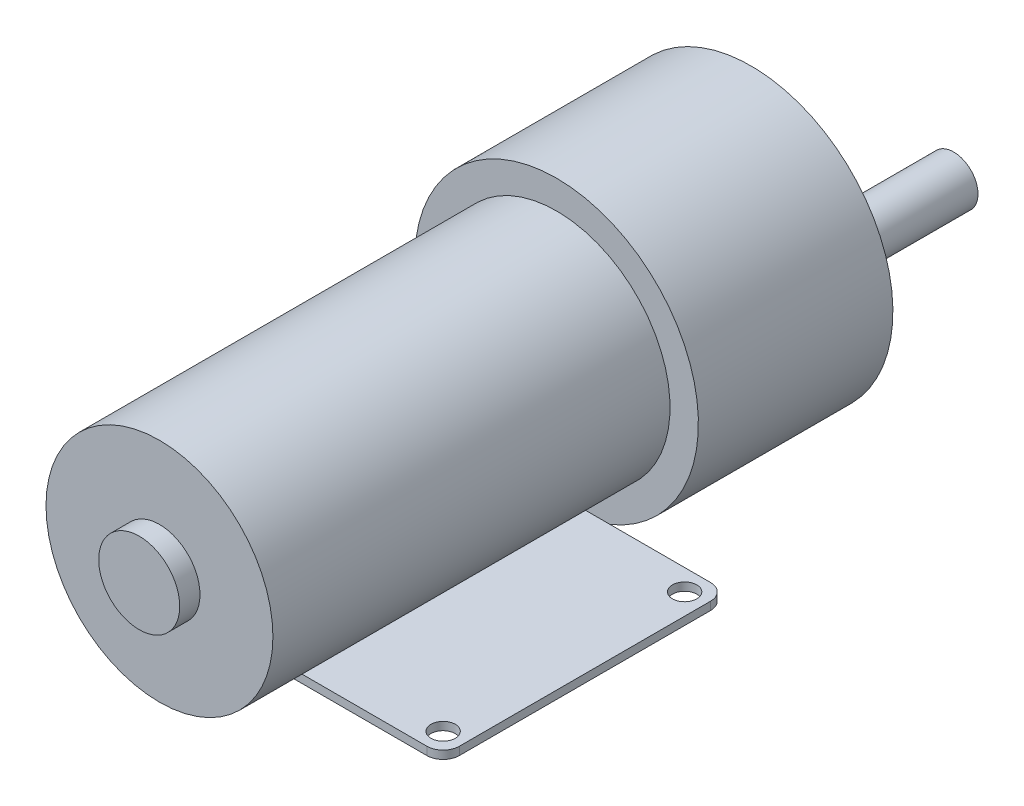
SolidWorks part; units mm, degrees
ref_plane "Plan de face" through (0, 0, 0) normal (0, 0, 1) x (1, 0, 0)
ref_plane "Plan de dessus" through (0, 0, 0) normal (0, 1, 0) x (1, 0, 0)
ref_plane "Plan de droite" through (0, 0, 0) normal (1, 0, 0) x (0, 0, -1)
sketch "Esquisse1" plane through (0, 0, 0) normal (0, 0, 1) x (1, 0, 0)
  circle A0 centre (9.6424, 0) radius 14
  dimension "D1" = 28
extrude "Boss.-Extru.1" add sketch "Esquisse1" along normal blind 49
sketch "Esquisse2" plane through (0, 0, 49) normal (0, 0, 1) x (1, 0, 0)
  circle A0 centre (9.6424, 0) radius 5
  dimension "D1" = 10
extrude "Boss.-Extru.2" add sketch "Esquisse2" along normal blind 2.5
sketch "Esquisse3" plane through (0, 0, 0) normal (0, 0, -1) x (-1, 0, 0)
  circle A0 centre (-9.6424, 0) radius 17.5
extrude "Boss.-Extru.3" add sketch "Esquisse3" along normal blind 24
sketch "Esquisse4" plane through (0, 0, -24) normal (0, 0, -1) x (-1, 0, 0)
  circle A0 centre (-9.6424, -7.2) radius 6
  circle A1 centre (-9.6424, 0) radius 17.5 construction
  dimension "D1" = 12
  dimension "D2" = 7.2
extrude "Boss.-Extru.4" add sketch "Esquisse4" along normal blind 10 contours A0
sketch "Esquisse5" plane through (0, 0, -34) normal (0, 0, -1) x (-1, 0, 0)
  circle A0 centre (-9.6424, -7.2) radius 3
extrude "Boss.-Extru.5" add sketch "Esquisse5" along normal blind 15
sketch "Esquisse7" plane through (0, 0, -49) normal (0, 0, -1) x (-1, 0, 0)
  line L0 (-11.3007, -9.7) -> (-7.9841, -9.7)
  arc A0 (-7.9841, -9.7) -> (-11.3007, -9.7) centre (-9.6424, -7.2) ccw
  circle A1 centre (-9.6424, -7.2) radius 3 construction
  circle A2 centre (-9.6424, -7.2) radius 3 construction
  dimension "D2" = 3
  dimension "D1" = 2.5
extrude "Enlèv. mat.-Extru.1" cut sketch "Esquisse7" against normal blind 12 flip side to cut
sketch "Esquisse8" plane through (0, 0, 0) normal (0, 0, 1) x (1, 0, 0)
  line L1 (9.6424, -16.2048) -> (30.6424, -16.2048)
  line L3 (9.6424, -17.2048) -> (30.6424, -17.2048)
  line L4 (30.6424, -16.2048) -> (30.6424, -17.2048)
  line L5 (9.6424, -16.2048) -> (-11.3576, -16.2048)
  line L7 (9.6424, -17.2048) -> (-11.3576, -17.2048)
  line L8 (-11.3576, -16.2048) -> (-11.3576, -17.2048)
  dimension "D1" = 21
  dimension "D2" = 21
  dimension "D4" = 1
extrude "Boss.-Extru.6" add sketch "Esquisse8" along normal blind 35
fillet "Congé1" radius 2 4 edges at (30.6424, -16.7048, 0) (30.6424, -16.7048, 35) (-11.3576, -16.7048, 0) (-11.3576, -16.7048, 35)
sketch "Esquisse9" plane through (0, -17.2048, 0) normal (0, -1, 0) x (1, 0, 0)
  line L0 (30.6424, 33) -> (30.6424, 2) construction
  line L1 (-9.3576, 35) -> (28.6424, 35) construction
  line L2 (-11.3576, 33) -> (-11.3576, 2) construction
  line L3 (-9.3576, 0) -> (6.4416, 0) construction
  line L4 (12.8433, 0) -> (28.6424, 0) construction
  circle A0 centre (28.0424, 32.4) radius 1.5
  circle A1 centre (-8.7576, 32.4) radius 1.5
  circle A2 centre (-8.7576, 2.6) radius 1.5
  circle A3 centre (28.0424, 2.6) radius 1.5
  dimension "D1" = 3
  dimension "D2" = 2.6
  dimension "D3" = 2.6
  dimension "D4" = 3
  dimension "D6" = 2.6
  dimension "D7" = 3
  dimension "D8" = 2.6
  dimension "D9" = 2.6
  dimension "D10" = 3
  dimension "D11" = 2.6
  dimension "D12" = 2.6
  dimension "D5" = 2.6
extrude "Enlèv. mat.-Extru.2" cut sketch "Esquisse9" against normal blind 35
